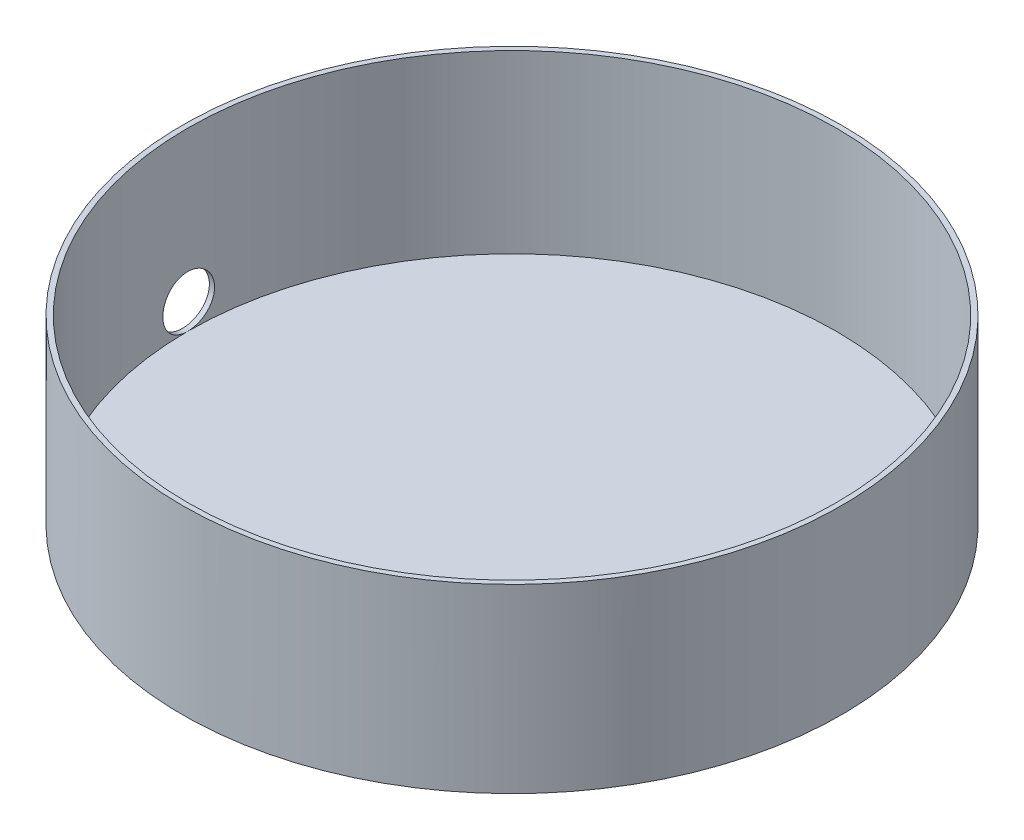
SolidWorks part; units mm, degrees
ref_plane "Front Plane" through (0, 0, 0) normal (0, 0, 1) x (1, 0, 0)
ref_plane "Top Plane" through (0, 0, 0) normal (0, 1, 0) x (1, 0, 0)
ref_plane "Right Plane" through (0, 0, 0) normal (1, 0, 0) x (0, 0, -1)
sketch "Sketch1" plane through (0, 0, 0) normal (0, 1, 0) x (1, 0, 0)
  circle A0 centre (0, 0) radius 125.3
  circle A1 centre (0, 0) radius 127.3
  point P2 (0, 0)
  dimension "D1" = 250.6
  dimension "D2" = 2
extrude "Boss-Extrude1" add sketch "Sketch1" along normal blind 68
sketch "Sketch3" plane through (0, 0, 0) normal (1, 0, 0) x (0, 0, -1)
  line L0 (-125.3, 0) -> (125.3, 0) construction
  line L1 (0, 10) -> (0, 0) construction
  circle A0 centre (0, 10) radius 10
  dimension "D1" = 20
sketch "Sketch4" plane through (0, 0, 0) normal (0, -1, 0) x (1, 0, 0)
  circle A0 centre (0, 0) radius 127.3 construction
  circle A1 centre (0, 0) radius 127.3
extrude "Boss-Extrude2" add sketch "Sketch4" along normal blind 2
extrude "Cut-Extrude3" cut sketch "Sketch3" against normal through all
